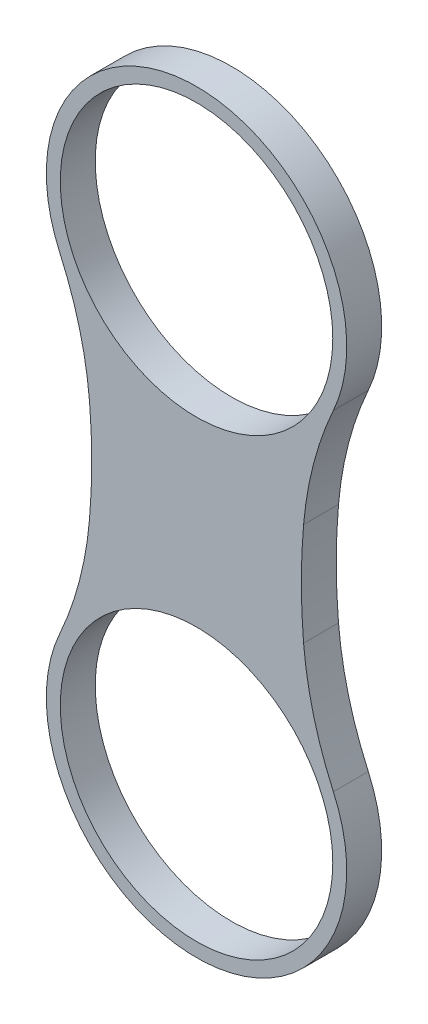
SolidWorks part; units mm, degrees
ref_plane "Спереди" through (0, 0, 0) normal (0, 0, 1) x (1, 0, 0)
ref_plane "Сверху" through (0, 0, 0) normal (0, 1, 0) x (1, 0, 0)
ref_plane "Справа" through (0, 0, 0) normal (1, 0, 0) x (0, 0, -1)
sketch "Эскиз1" plane through (0, 0, 0) normal (0, 0, 1) x (1, 0, 0)
  circle A0 centre (0, 0) radius 3.9
  arc A1 (3.917, -1.7741) -> (-3.917, -1.7741) centre (0, 0) ccw
  circle A2 centre (0, -13) radius 3.9
  arc A3 (-3.917, -11.2259) -> (3.917, -11.2259) centre (0, -13) ccw
  arc A4 (-3.064, -5.0304) -> (-3.064, -7.9696) centre (-19.9, -6.5) cw
  arc A5 (3.064, -5.0304) -> (3.064, -7.9696) centre (19.9, -6.5) ccw
  arc A6 (-3.917, -11.2259) -> (-3.064, -7.9696) centre (-13.0261, -7.1) ccw
  arc A7 (-3.064, -5.0304) -> (-3.917, -1.7741) centre (-13.0261, -5.9) ccw
  arc A8 (3.917, -1.7741) -> (3.064, -5.0304) centre (13.0261, -5.9) ccw
  arc A9 (3.064, -7.9696) -> (3.917, -11.2259) centre (13.0261, -7.1) ccw
  dimension "D1" = 10
  dimension "D2" = 10
  dimension "D3" = 10
  dimension "D4" = 10
  dimension "D5" = 7.8
  dimension "D6" = 7.8
  dimension "D7" = 16.9
  dimension "D8" = 16.9
  dimension "D9" = 3.064
  dimension "D10" = 3.064
  dimension "D11" = 3.064
  dimension "D12" = 3.064
extrude "Вытянуть1" add sketch "Эскиз1" along normal blind 1
